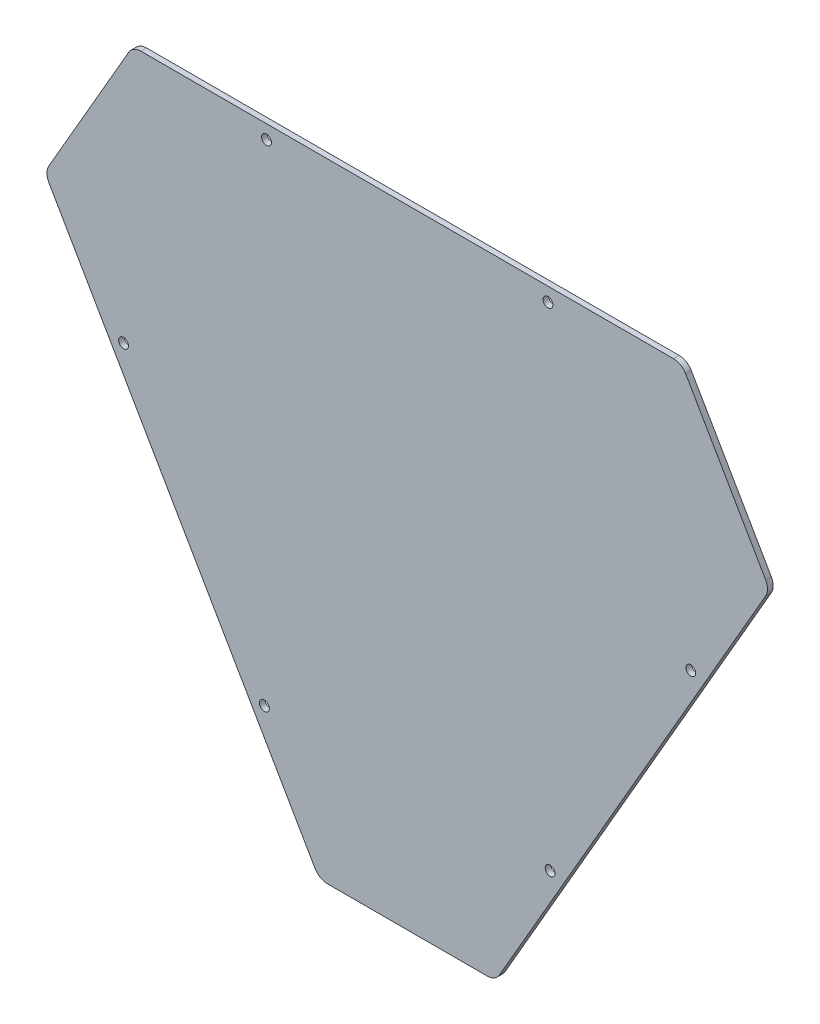
SolidWorks part; units mm, degrees
ref_plane "Piano frontale" through (0, 0, 0) normal (0, 0, 1) x (1, 0, 0)
ref_plane "Piano superiore" through (0, 0, 0) normal (0, 1, 0) x (1, 0, 0)
ref_plane "Piano destro" through (0, 0, 0) normal (1, 0, 0) x (0, 0, -1)
sketch "Schizzo1" plane through (0, 0, 0) normal (0, 0, 1) x (-1, 0, 0)
  line L0 (461.7599, 166.3003) -> (364.2237, 335.1126)
  line L1 (239.0164, 335.1126) -> (44.0888, -2.6373)
  line L15 (106.6562, -111.0074) -> (496.6562, -111.0074)
  line L20 (461.7599, 166.3003) -> (559.2599, -2.5747)
  line L24 (496.6562, -111.0074) -> (559.2599, -2.5747)
  line L25 (301.6562, -111.0074) -> (301.6562, 400.3066) construction
  line L26 (461.7599, 166.3003) -> (19.0856, -89.3933) construction
  line L27 (44.0888, -2.6373) -> (106.6924, -111.07)
  line L28 (364.2237, 335.1126) -> (239.0164, 335.1126)
  point P32 (301.6562, 73.8226)
  point P39 (301.6562, 73.8226)
  dimension "D3" = 3
extrude "Estrusione-Estrusione1" add sketch "Schizzo1" along normal blind 4 contours L0 L28 L1 L27 L15 L24 L20
fillet "Raccordo1" radius 10 6 edges at (-496.6562, 111.0074, 2) (-559.2599, 2.5747, 2) (-364.2237, -335.1126, 2) (-239.0164, -335.1126, 2) (-44.0888, 2.6373, 2) (-106.6562, 111.0074, 2)
sketch "Schizzo2" plane through (0, 0, 4) normal (0, 0, 1) x (1, 0, 0)
  line L0 (-553.5608, 12.4457) -> (-352.749, -335.1126) construction
  line L1 (-461.7599, -166.3003) -> (-367.111, -330.1153) construction
  line L2 (-461.7599, -166.3003) -> (-556.3731, -2.4253) construction
  line L3 (-358.4523, -335.1126) -> (-244.791, -335.1126) construction
  line L4 (-499.543, 106.0074) -> (-556.3731, 7.5747) construction
  line L5 (-301.6562, 111.0074) -> (-301.6217, -335.1126) construction
  line L6 (-112.4297, 111.0074) -> (-490.8827, 111.0074) construction
  line L7 (-141.5521, -166.2367) -> (-527.9581, 56.791) construction
  line L8 (-236.13, -330.1112) -> (-46.9742, -2.3622) construction
  line L9 (-75.3722, 56.8219) -> (-461.7599, -166.3003) construction
  line L10 (-46.975, 7.6364) -> (-103.7695, 106.0074) construction
  line L11 (-100.961, 101.1925) -> (-502.3612, 101.0635) construction
  line L12 (-250.404, -335.1439) -> (-49.8156, 12.5434) construction
  circle A0 centre (-503.1828, -74.747) radius 3.5
  circle A1 centre (-403.1271, -247.9199) radius 3.5
  circle A2 centre (-201.6611, 101.1601) radius 3.5
  circle A3 centre (-401.6611, 101.0958) radius 3.5
  circle A4 centre (-200.0819, -247.9189) radius 3.5
  circle A5 centre (-100.1376, -74.6817) radius 3.5
  point P10 (-453.1549, -161.3334)
  point P28 (-301.6419, -73.8352)
  point P44 (-301.6419, -73.8352)
  dimension "D2" = 7
  dimension "D1" = 10
  dimension "D3" = 200
  dimension "D4" = 100
  dimension "D5" = 3
extrude "Taglio-Estrusione1" cut sketch "Schizzo2" against normal blind 10
